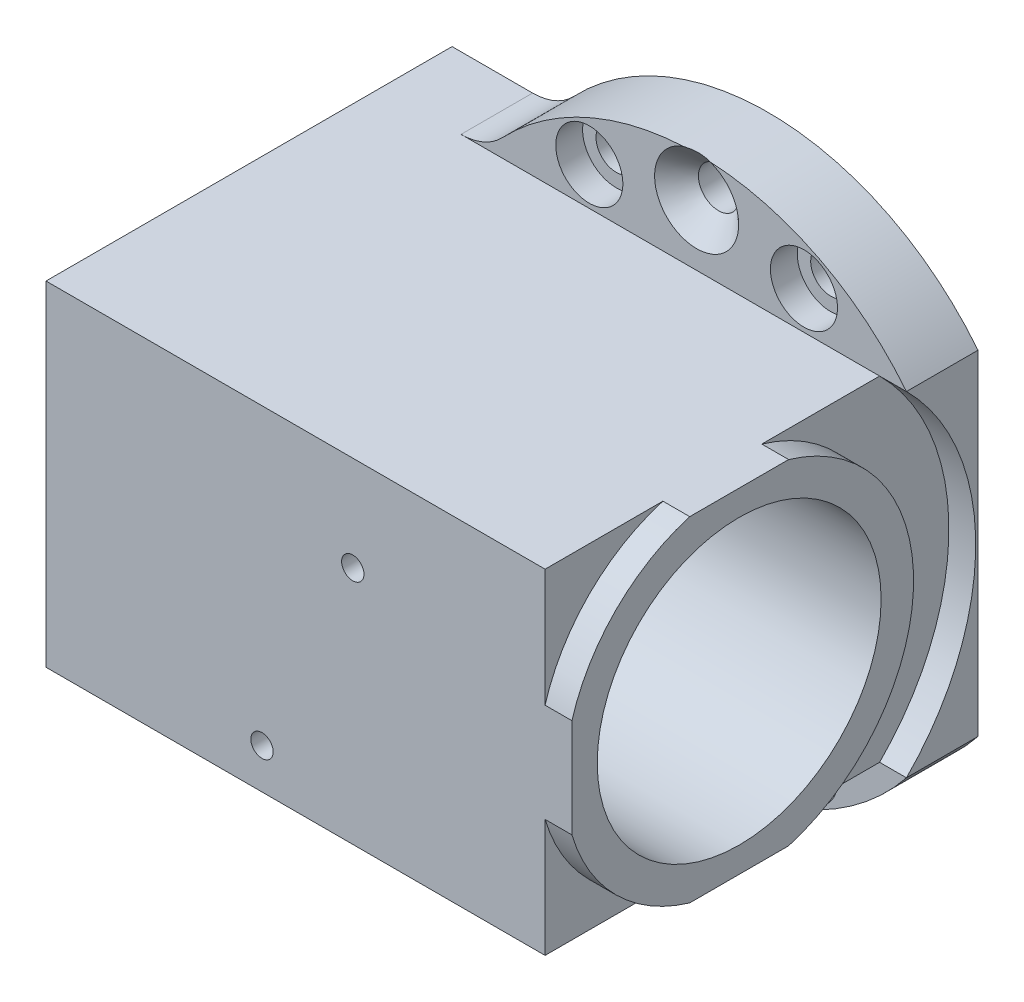
SolidWorks part; units mm, degrees
ref_plane "Front Plane" through (0, 0, 0) normal (0, 0, 1) x (1, 0, 0)
ref_plane "Top Plane" through (0, 0, 0) normal (0, 1, 0) x (1, 0, 0)
ref_plane "Right Plane" through (0, 0, 0) normal (1, 0, 0) x (0, 0, -1)
ref_plane "Plane1" through (0, 0, 8) normal (0, 0, 1) x (1, 0, 0)
sketch "Sketch1" plane through (0, 0, 8) normal (0, 0, 1) x (1, 0, 0)
  line L0 (-23.4587, 18.7) -> (-23.4587, -18.7)
  line L1 (23.4587, -18.7) -> (35.3413, -18.7)
  line L2 (35.3413, -18.7) -> (35.3413, 18.7)
  line L3 (35.3413, 18.7) -> (23.4587, 18.7)
  arc A0 (-23.4587, -18.7) -> (23.4587, -18.7) centre (0, 0) ccw
  arc A1 (23.4587, 18.7) -> (-23.4587, 18.7) centre (0, 0) ccw
extrude "Boss-Extrude1" add sketch "Sketch1" against normal blind 8
ref_plane "Plane2" through (-23.4587, 0, 0) normal (-1, 0, 0) x (0, -1, 0)
ref_plane "Plane3" through (-20.4587, 0, 0) normal (1, 0, 0) x (0, 0, -1)
sketch "Sketch3" plane through (-20.4587, 0, 0) normal (1, 0, 0) x (0, 0, -1)
  line L0 (-8, 18.7) -> (-8, -18.7)
  arc A0 (-8, -18.7) -> (-8, 18.7) centre (-26.7, 0) ccw
extrude "Cut-Extrude1" cut sketch "Sketch3" against normal up to surface up to plane "Plane2"
sketch "Sketch4" plane through (0, 0, 8) normal (0, 0, 1) x (1, 0, 0)
  line L0 (-20.4587, -18.7) -> (-20.4587, 18.7)
  line L1 (-20.4587, 18.7) -> (35.3413, 18.7)
  line L2 (35.3413, 18.7) -> (35.3413, -18.7)
  line L3 (35.3413, -18.7) -> (-20.4587, -18.7)
extrude "Boss-Extrude2" add sketch "Sketch4" along normal blind 37.4
sketch "Sketch5" plane through (-20.4587, 0, 0) normal (-1, 0, 0) x (0, 0, 1)
  line L0 (21.1719, 18.7) -> (45.4, 18.7)
  line L1 (45.4, 18.7) -> (45.4, -18.7)
  line L2 (45.4, -18.7) -> (21.1719, -18.7)
  arc A0 (21.1719, -18.7) -> (21.1719, 18.7) centre (26.7, 0) cw
extrude "Boss-Extrude3" add sketch "Sketch5" along normal blind 3
sketch "Sketch6" plane through (-23.4587, 0, 0) normal (-1, 0, 0) x (0, 0, 1)
  line L0 (45.4, -18.7) -> (45.4, -5.5281)
  line L1 (32.2281, -18.7) -> (45.4, -18.7)
  arc A0 (45.4, -5.5281) -> (32.2281, -18.7) centre (26.7, 0) cw
extrude "Cut-Extrude2" cut sketch "Sketch6" against normal blind 3
sketch "Sketch7" plane through (-23.4587, 0, 0) normal (-1, 0, 0) x (0, 0, 1)
  line L0 (45.4, 18.7) -> (32.2281, 18.7)
  line L1 (45.4, 5.5281) -> (45.4, 18.7)
  arc A0 (32.2281, 18.7) -> (45.4, 5.5281) centre (26.7, 0) cw
extrude "Cut-Extrude3" cut sketch "Sketch7" against normal blind 3
ref_plane "Plane4" through (0, 0, 26.7) normal (0, 0, 1) x (1, 0, 0)
sketch "Sketch8" plane through (0, 0, 26.7) normal (0, 0, 1) x (1, 0, 0)
  line L0 (-23.4587, 15.8686) -> (-23.4587, 0)
  line L1 (-23.4587, 0) -> (35.3413, 0)
  line L2 (35.3413, 0) -> (35.3413, 15.8687)
  line L3 (35.3413, 15.8687) -> (9.9413, 15.8687)
  line L4 (9.9413, 15.8687) -> (9.9413, 13.5)
  line L5 (9.9413, 13.5) -> (1.9413, 13.5)
  line L6 (1.9413, 13.5) -> (1.9413, 15.8686)
  line L7 (1.9413, 15.8686) -> (-23.4587, 15.8686)
  line L8 (-23.4587, 0) -> (35.3413, 0) construction
revolve "Cut-Revolve1" cut sketch "Sketch8" angle 360 about L8
hole_wizard "CSK for #8 Flat Head Machine Screw (100)1" positions "Sketch10" profile "Sketch9" countersink size "#8" standard "ANSI Inch"
sketch "Sketch10" plane through (0, 0, 8) normal (0, 0, 1) x (1, 0, 0)
  point P0 (0, 25.5)
  point P1 (0, -25.5)
sketch "Sketch9" plane through (0, 25.5, 8) normal (1, 0, 0) x (0, -1, 0)
  line L0 (0, 0) -> (0, 8)
  line L1 (0, 8) -> (2.25, 8)
  line L2 (2.25, 8) -> (2.25, 2.45)
  line L3 (2.25, 2.45) -> (4.7, 0)
  line L5 (4.7, 0) -> (0, 0)
  line L6 (-2.25, 2.45) -> (-4.7, 0) construction
  line L11 (0, -6.35) -> (0, 107.95) construction
  dimension "Thru Hole Dia." = 4.5
  dimension "Thru Hole Depth" = 8
  dimension "Near C'Sink Dia." = 9.4
  dimension "Near C'Sink Angle" = 90
hole_wizard "#4 Clearance Hole1" positions "Sketch12" profile "Sketch11" hole size "#4" standard "ANSI Inch"
sketch "Sketch12" plane through (0, -18.7, 0) normal (0, -1, 0) x (-1, 0, 0)
  point P0 (12.4587, -39.4)
  point P1 (-29.4413, -39.4)
  point P2 (-29.4413, -5.9)
sketch "Sketch11" plane through (-12.4587, -18.7, 39.4) normal (1, 0, 0) x (0, 0, -1)
  line L0 (0, 0) -> (0, 6)
  line L1 (0, 6) -> (1.65, 6)
  line L2 (1.65, 6) -> (1.65, 0)
  line L5 (1.65, 0) -> (0, 0)
  line L10 (0, 6) -> (-1.65, 6) construction
  line L11 (0, -6.35) -> (0, 107.95) construction
  dimension "Hole Dia." = 3.3
  dimension "Hole Depth" = 6
  dimension "Drill Angle" = 180
hole_wizard "CBORE for #8 Binding Head Machine Screw1" positions "Sketch14" profile "Sketch13" counterbore size "#8" standard "ANSI Inch"
sketch "Sketch14" plane through (0, 0, 8) normal (0, 0, 1) x (1, 0, 0)
  point P0 (12, 22.95)
  point P1 (-12, 22.95)
  point P2 (-12, -22.95)
  point P3 (12, -22.95)
sketch "Sketch13" plane through (12, 22.95, 8) normal (1, 0, 0) x (0, -1, 0)
  line L0 (0, 0) -> (0, 8)
  line L1 (0, 8) -> (2.25, 8)
  line L3 (2.25, 8) -> (2.25, 3)
  line L4 (2.25, 3) -> (3.75, 3)
  line L5 (3.75, 3) -> (3.75, 0)
  line L7 (3.75, 0) -> (0, 0)
  line L11 (0, -6.35) -> (0, 107.95) construction
  dimension "Thru Hole Dia." = 4.5
  dimension "Thru Hole Depth" = 8
  dimension "C'Bore Dia." = 7.5
  dimension "C'Bore Depth" = 3
hole_wizard "#2 Clearance Hole1" positions "Sketch16" profile "Sketch15" hole size "#2" standard "ANSI Inch"
sketch "Sketch16" plane through (0, 0, 45.4) normal (0, 0, 1) x (1, 0, 0)
  point P0 (-0.8087, 14.63)
sketch "Sketch15" plane through (-0.8087, 14.63, 45.4) normal (1, 0, 0) x (0, -1, 0)
  line L0 (0, 0) -> (0, 6)
  line L1 (0, 6) -> (1.25, 6)
  line L2 (1.25, 6) -> (1.25, 0)
  line L5 (1.25, 0) -> (0, 0)
  line L10 (0, 6) -> (-1.25, 6) construction
  line L11 (0, -6.35) -> (0, 107.95) construction
  dimension "Hole Dia." = 2.5
  dimension "Hole Depth" = 6
  dimension "Drill Angle" = 180
hole_wizard "#2 Clearance Hole2" positions "Sketch18" profile "Sketch17" hole size "#2" standard "ANSI Inch"
sketch "Sketch18" plane through (0, 0, 45.4) normal (0, 0, 1) x (1, 0, 0)
  point P0 (15.9651, -3.2)
sketch "Sketch17" plane through (15.9651, -3.2, 45.4) normal (1, 0, 0) x (0, -1, 0)
  line L0 (0, 0) -> (0, 3.1573)
  line L1 (0, 3.1573) -> (1.25, 3.1573)
  line L2 (1.25, 3.1573) -> (1.25, 0)
  line L5 (1.25, 0) -> (0, 0)
  line L11 (0, -6.35) -> (0, 107.95) construction
  dimension "Thru Hole Dia." = 2.5
  dimension "Thru Hole Depth" = 3.1573
fillet "Fillet1" radius 6.35 1 edges at (23.4587, 18.7, 4)
sketch "Sketch20" plane through (0, 0, 45.4) normal (0, 0, 1) x (1, 0, 0)
  line L0 (35.3413, 18.7) -> (-20.4587, 18.7) construction
  line L1 (-20.4587, -18.7) -> (35.3413, -18.7) construction
  line L2 (-23.4587, 18.7) -> (-23.4587, 5.5281) construction
  point P0 (1.0413, 8.0737)
  point P1 (11.1917, -14.199)
  dimension "D1" = 10.6263
  dimension "D2" = 4.501
  dimension "D3" = 24.4766
  dimension "D4" = 24.5
hole_wizard "M3x0.5 Tapped Hole1" positions "3DSketch1" profile "Sketch23" tap size "M3x0.5" standard "ANSI Metric"
sketch3d "3DSketch1"
  point P0 (1.0413, 8.0737, 45.4)
  point P3 (11.1917, -14.199, 45.4)
sketch "Sketch23" plane through (1.0413, 8.0737, 45.4) normal (1, 0, 0) x (0, -1, 0)
  line L0 (0, 0) -> (0, 4.7511)
  line L1 (0, 4.7511) -> (1.25, 4)
  line L2 (1.25, 4) -> (1.25, 0)
  line L5 (1.25, 0) -> (0, 0)
  line L10 (0, 4.7511) -> (-1.25, 4) construction
  line L11 (0, -6.35) -> (0, 107.95) construction
  dimension "Tap Drill Dia." = 2.5
  dimension "Tap Drill Depth" = 4
  dimension "Drill Angle" = 118
cosmetic thread "Hole Thread1" parameters "D1"=4, "D2"=3
cosmetic thread "Hole Thread2" parameters "D1"=4, "D2"=3
fillet "Fillet2" radius 6.35 1 edges at (23.4587, -18.7, 4)
mirror "镜向2" about plane through (35.3413, -18.7, 0) normal (1, 0, 0) of bodies 117
sketch "草图2" plane through (0, 0, 45.4) normal (0, 0, 1) x (1, 0, 0)
  line L6 (35.3413, -50.2624) -> (-48.4959, -50.2624)
  line L7 (35.3413, -50.2624) -> (35.3413, 46.114)
  line L8 (35.3413, 46.114) -> (-48.4959, 46.114)
  line L9 (-48.4959, -50.2624) -> (-48.4959, 46.114)
  point P1 (-45.5148, 46.114)
  point P2 (-48.4959, -50.2624)
extrude "切除-拉伸1" cut sketch "草图2" against normal through all
